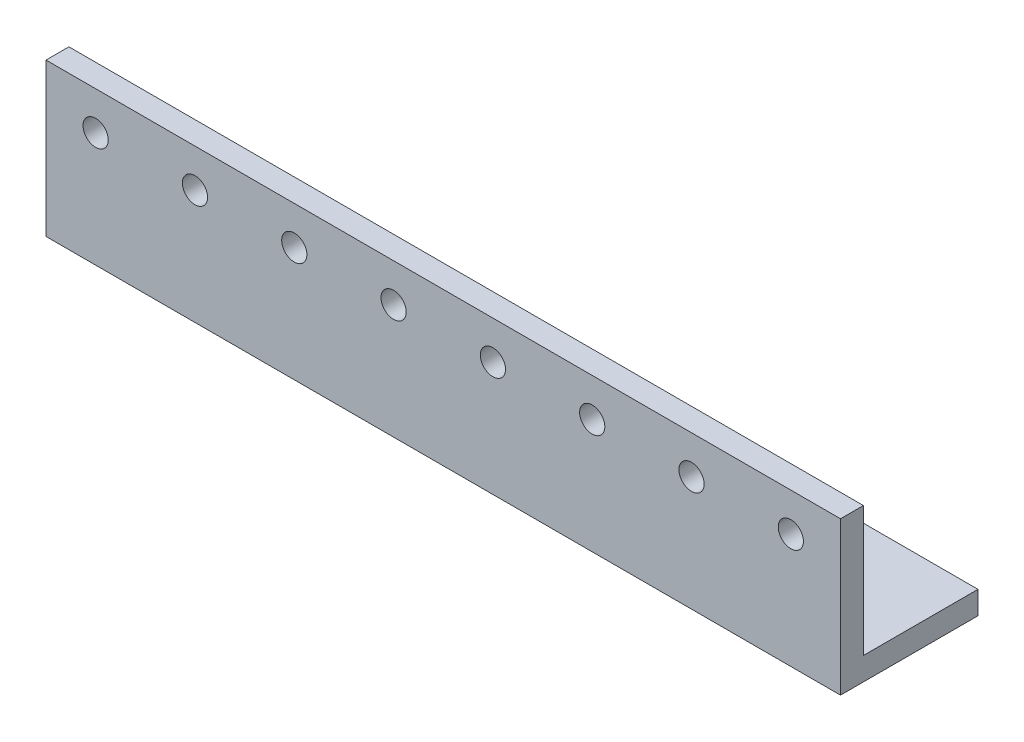
SolidWorks part; units mm, degrees
ref_plane "Front Plane" through (0, 0, 0) normal (0, 0, 1) x (1, 0, 0)
ref_plane "Top Plane" through (0, 0, 0) normal (0, 1, 0) x (1, 0, 0)
ref_plane "Right Plane" through (0, 0, 0) normal (1, 0, 0) x (0, 0, -1)
sketch "Sketch1" plane through (0, 0, 0) normal (0, 0, 1) x (1, 0, 0)
  circle A0 centre (0, 0) radius 6.5
  dimension "D1" = 13
sketch "Sketch2" plane through (0, 0, 0) normal (0, 0, 1) x (1, 0, 0)
  line L1 (-52, -20) -> (52, -20)
  line L2 (-52, -20) -> (-52, 0)
  line L3 (-52, 0) -> (52, 0)
  line L4 (52, -20) -> (52, 0)
  dimension "D1" = 104
  dimension "D2" = 20
extrude "Boss-Extrude1" add sketch "Sketch2" along normal blind 3
hole_wizard "M4x0.7 Tapped Hole1" positions "Sketch3" profile "Sketch4" tap size "M4x0.7" standard "ANSI Metric" end condition through all
sketch "Sketch3" plane through (0, 0, 3) normal (0, 0, 1) x (1, 0, 0)
  line L0 (-45.5, -5) -> (45.5, -5) construction
  line L4 (0, 0) -> (0, -5) construction
  line L5 (52, 0) -> (-52, 0) construction
  point P5 (-45.5, -5)
  point P6 (45.5, -5)
  point P11 (-32.5, -5)
  point P12 (-19.5, -5)
  point P13 (-6.5, -5)
  point P14 (6.5, -5)
  point P15 (19.5, -5)
  point P16 (32.5, -5)
  point P29 (47.4902, -5)
  dimension "D1" = 5
  dimension "D2" = 13
sketch "Sketch4" plane through (-45.5, -5, 3) normal (1, 0, 0) x (0, -1, 0)
  line L0 (0, 0) -> (0, 3)
  line L1 (0, 3) -> (1.65, 3)
  line L2 (1.65, 3) -> (1.65, 0)
  line L5 (1.65, 0) -> (0, 0)
  line L11 (0, -6.35) -> (0, 107.95) construction
  dimension "Thru Tap Drill Dia." = 3.3
  dimension "Thru Tap Drill Depth" = 3
cosmetic thread "Hole Thread1" parameters "D2"=4
cosmetic thread "Hole Thread2" parameters "D2"=4
cosmetic thread "Hole Thread3" parameters "D2"=4
cosmetic thread "Hole Thread4" parameters "D2"=4
cosmetic thread "Hole Thread5" parameters "D2"=4
cosmetic thread "Hole Thread6" parameters "D2"=4
cosmetic thread "Hole Thread7" parameters "D2"=4
cosmetic thread "Hole Thread8" parameters "D2"=4
sketch "Sketch5" plane through (0, 0, 0) normal (0, 0, -1) x (-1, 0, 0)
  line L0 (52, 0) -> (52, -20) construction
  line L1 (-52, -20) -> (52, -20)
  line L2 (-52, -20) -> (-52, -17)
  line L3 (-52, -17) -> (52, -17)
  line L4 (52, -20) -> (52, -17)
  dimension "D1" = 3
extrude "Boss-Extrude2" add sketch "Sketch5" along normal blind 15
hole_wizard "CSK for #10 Flat Head Machine Screw (100)1" positions "Sketch6" profile "Sketch7" countersink size "#10" standard "ANSI Inch" end condition through all
sketch "Sketch6" plane through (0, -17, 0) normal (0, 1, 0) x (1, 0, 0)
  line L0 (-37.5, 7.5) -> (37.5, 7.5) construction
  line L3 (0, 7.5) -> (0, 0) construction
  line L4 (-6.5, 0) -> (6.5, 0) construction
  line L6 (0, 7.5) -> (0, 15) construction
  line L7 (-52, 15) -> (52, 15) construction
  point P0 (37.5, 7.5)
  point P2 (0, 7.5)
  point P4 (-37.5, 7.5)
  dimension "D1" = 75
sketch "Sketch7" plane through (37.5, -17, -7.5) normal (1, 0, 0) x (0, 0, 1)
  line L0 (0, 0) -> (0, 3)
  line L1 (0, 3) -> (2.5527, 3)
  line L2 (2.5527, 3) -> (2.5527, 1.9608)
  line L3 (2.5527, 1.9608) -> (4.8895, 0)
  line L5 (4.8895, 0) -> (0, 0)
  line L6 (-2.5527, 1.9608) -> (-4.8895, 0) construction
  line L11 (0, -6.35) -> (0, 107.95) construction
  dimension "Thru Hole Dia." = 5.1054
  dimension "Thru Hole Depth" = 3
  dimension "Near C'Sink Dia." = 9.779
  dimension "Near C'Sink Angle" = 100
